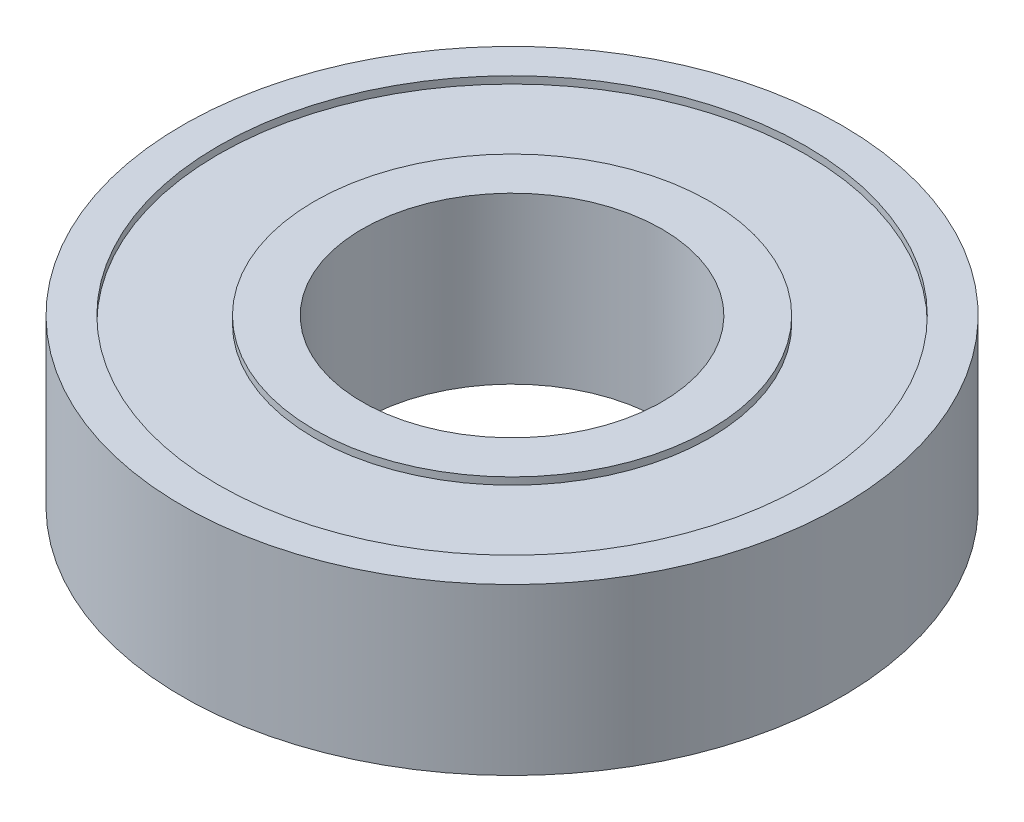
SolidWorks part; units mm, degrees
ref_plane "Front Plane" through (0, 0, 0) normal (0, 0, 1) x (1, 0, 0)
ref_plane "Top Plane" through (0, 0, 0) normal (0, 1, 0) x (1, 0, 0)
ref_plane "Right Plane" through (0, 0, 0) normal (1, 0, 0) x (0, 0, -1)
sketch "Sketch1" plane through (0, 0, 0) normal (0, 0, 1) x (1, 0, 0)
  line L0 (7.9375, 8.382) -> (7.9375, -0.381)
  line L1 (7.9375, -0.381) -> (10.4775, -0.381)
  line L2 (10.4775, -0.381) -> (10.4775, 0)
  line L3 (10.4775, 0) -> (15.5575, 0)
  line L4 (15.5575, 0) -> (15.5575, -0.381)
  line L5 (15.5575, -0.381) -> (17.4625, -0.381)
  line L6 (17.4625, -0.381) -> (17.4625, 8.382)
  line L7 (7.9375, 4.0005) -> (17.4625, 4.0005) construction
  line L8 (15.5575, 8.382) -> (17.4625, 8.382)
  line L9 (15.5575, 8.001) -> (15.5575, 8.382)
  line L10 (10.4775, 8.001) -> (15.5575, 8.001)
  line L11 (10.4775, 8.382) -> (10.4775, 8.001)
  line L12 (7.9375, 8.382) -> (10.4775, 8.382)
  line L13 (0, 0) -> (0, 1.9273) construction
  dimension "D1" = 7.9375
  dimension "D2" = 17.4625
  dimension "D3" = 2.54
  dimension "D4" = 1.905
  dimension "D5" = 0.381
  dimension "D6" = 4.3815
revolve "Revolve1" add sketch "Sketch1" angle 360 about L13
